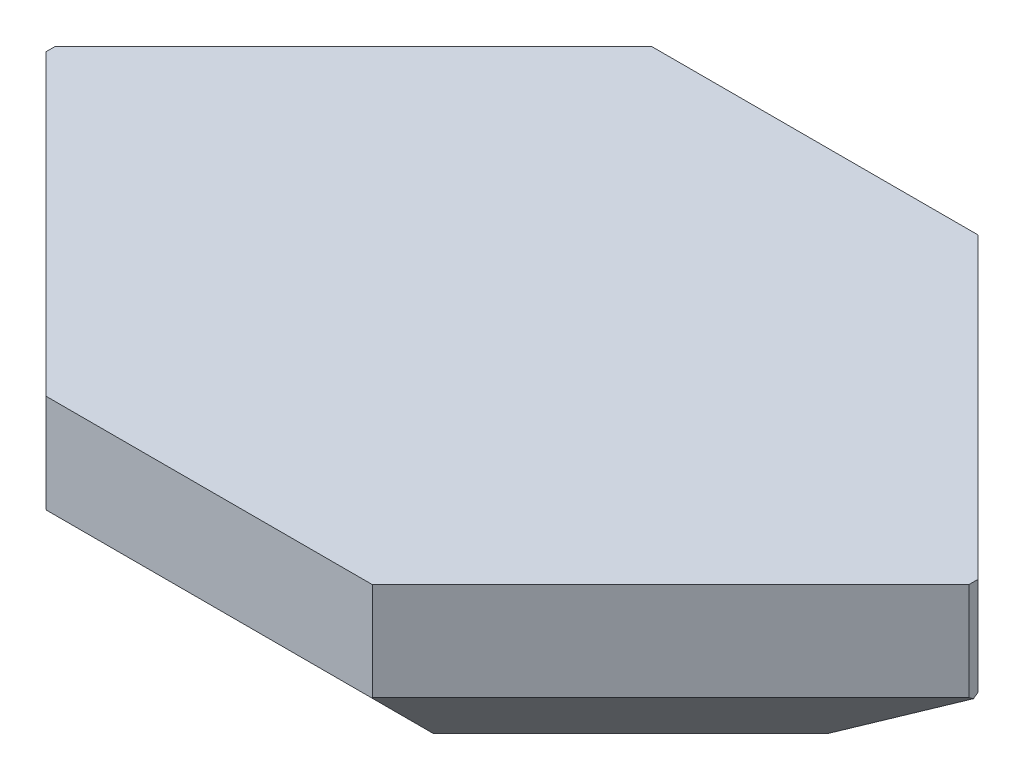
SolidWorks part; units mm, degrees
ref_plane "Front Plane" through (0, 0, 0) normal (0, 0, 1) x (1, 0, 0)
ref_plane "Top Plane" through (0, 0, 0) normal (0, 1, 0) x (1, 0, 0)
ref_plane "Right Plane" through (0, 0, 0) normal (1, 0, 0) x (0, 0, -1)
sketch "Sketch1" plane through (0, 0, 0) normal (0, 1, 0) x (1, 0, 0)
  line L4 (-25.4, 47.1463) -> (25.4, 47.1463)
  line L5 (25.4, 47.1463) -> (72.5463, 0)
  line L6 (72.5463, 0) -> (25.4, -47.1463)
  line L7 (25.4, -47.1463) -> (-25.4, -47.1463)
  line L8 (-25.4, -47.1463) -> (-72.5463, 0)
  line L9 (-72.5463, 0) -> (-25.4, 47.1463)
  line L10 (0, 47.1463) -> (0, -47.1463) construction
  point P9 (0, 0)
  dimension "D1" = 66.675
  dimension "D2" = 50.8
extrude "Boss-Extrude1" add sketch "Sketch1" along normal blind 76.2
ref_plane "Plane1" through (0, 14.5268, 14.5268) normal (0, 0.7071, 0.7071) x (-1, 0, 0)
ref_plane "Plane2" through (0, 10.0367, 10.0367) normal (0, 0.7071, 0.7071) x (-1, 0, 0)
other "SurfaceCut1"
ref_plane "Plane3" through (0, 14.5268, -14.5268) normal (0, 0.7071, -0.7071) x (1, 0, 0)
ref_plane "Plane4" through (0, 10.0367, -10.0367) normal (0, 0.7071, -0.7071) x (1, 0, 0)
other "SurfaceCut2"
ref_plane "Plane5" through (0, 50.8, 0) normal (0, 1, 0) x (1, 0, 0)
other "SurfaceCut3"
chamfer "Chamfer1" distance 16.51 angle 45 4 edges at (-57.183, 50.8, 15.3633) (-57.183, 50.8, -15.3633) (57.183, 50.8, 15.3633) (57.183, 50.8, -15.3633)
chamfer "Chamfer2" distance 1 angle 45 2 edges at (-72.5463, 71.755, 0) (72.5463, 71.755, 0)
sketch "Sketch2" plane through (0, 76.2, 0) normal (0, 1, 0) x (1, 0, 0)
  line L3 (-23.6828, 45.6816) -> (-69.3644, 0)
  line L4 (-69.3644, 0) -> (-23.6828, -45.6816)
  line L5 (-23.6828, -45.6816) -> (-23.6828, 45.6816)
  line L6 (-23.6828, 45.6816) -> (-69.3644, 0)
  line L7 (-69.3644, 0) -> (-23.6828, -45.6816)
  line L8 (-23.6828, -45.6816) -> (-23.6828, 45.6816)
  line L9 (69.3644, 0) -> (23.6828, 45.6816)
  line L10 (23.6827, -45.6816) -> (69.3644, 0)
  line L11 (23.6828, 45.6816) -> (23.6827, -45.6816)
  line L12 (69.3644, 0) -> (23.6828, 45.6816)
  line L13 (23.6827, -45.6816) -> (69.3644, 0)
  line L14 (23.6828, 45.6816) -> (23.6827, -45.6816)
  dimension "D1" = 0.25
  dimension "D2" = 0.25
sketch "Sketch5" plane through (0, 10.0367, -10.0367) normal (0, 0.7071, -0.7071) x (1, 0, 0)
  line L0 (0, -21.2511) -> (0, -86.5119) construction
  line L6 (-25.4, -20.544) -> (-71.8392, -53.3815)
  line L7 (-25.4, -20.544) -> (-71.8392, -53.3815)
  line L8 (-71.8392, -53.3815) -> (-71.8392, -54.3815)
  line L9 (-71.8392, -53.3815) -> (-71.8392, -54.3815)
  line L10 (-71.8392, -54.3815) -> (-25.4, -87.219)
  line L11 (-71.8392, -54.3815) -> (-25.4, -87.219)
  line L21 (-25.4, -87.219) -> (25.4, -87.219)
  line L22 (-25.4, -87.219) -> (25.4, -87.219)
  line L23 (25.4, -87.219) -> (71.8392, -54.3815)
  line L24 (25.4, -87.219) -> (71.8392, -54.3815)
  line L25 (71.8392, -54.3815) -> (71.8392, -53.3815)
  line L26 (71.8392, -54.3815) -> (71.8392, -53.3815)
  line L27 (71.8392, -53.3815) -> (25.4, -20.544)
  line L28 (71.8392, -53.3815) -> (25.4, -20.544)
  line L29 (25.4, -20.544) -> (-25.4, -20.544)
  line L30 (25.4, -20.544) -> (-25.4, -20.544)
  circle A0 centre (0, -53.8815) radius 1.905
  circle A1 centre (0, -53.8815) radius 3.81
  dimension "D2" = 3.81
  dimension "D3" = 7.62
  dimension "D1" = 0
ref_plane "Plane6" through (0, 36.9775, -36.9775) normal (0, 0.7071, -0.7071) x (1, 0, 0)
sketch "Sketch6" plane through (0, 36.9775, -36.9775) normal (0, 0.7071, -0.7071) x (1, 0, 0)
  line L0 (0, -86.5119) -> (0, -21.2511) construction
  line L6 (-25.4, -20.544) -> (-71.8392, -53.3815)
  line L7 (-25.4, -20.544) -> (-71.8392, -53.3815)
  line L8 (-71.8392, -53.3815) -> (-71.8392, -54.3815)
  line L9 (-71.8392, -53.3815) -> (-71.8392, -54.3815)
  line L10 (-71.8392, -54.3815) -> (-25.4, -87.219)
  line L11 (-71.8392, -54.3815) -> (-25.4, -87.219)
  line L21 (-25.4, -87.219) -> (25.4, -87.219)
  line L22 (-25.4, -87.219) -> (25.4, -87.219)
  line L23 (25.4, -87.219) -> (71.8392, -54.3815)
  line L24 (25.4, -87.219) -> (71.8392, -54.3815)
  line L25 (71.8392, -54.3815) -> (71.8392, -53.3815)
  line L26 (71.8392, -54.3815) -> (71.8392, -53.3815)
  line L27 (71.8392, -53.3815) -> (25.4, -20.544)
  line L28 (71.8392, -53.3815) -> (25.4, -20.544)
  line L29 (25.4, -20.544) -> (-25.4, -20.544)
  line L30 (25.4, -20.544) -> (-25.4, -20.544)
  circle A0 centre (0, -53.8815) radius 6.35
  dimension "D2" = 12.7
  dimension "D1" = 0
sketch "Sketch7" plane through (0, 76.2, 0) normal (0, 1, 0) x (1, 0, 0)
  line L2 (-22.225, -38.1) -> (22.225, -38.1) construction
  line L3 (-22.225, -38.1) -> (-22.225, 38.1) construction
  line L4 (-22.225, 38.1) -> (22.225, 38.1) construction
  line L5 (22.225, -38.1) -> (22.225, 38.1) construction
  line L6 (-22.225, -38.1) -> (22.225, 38.1) construction
  line L7 (-22.225, 38.1) -> (22.225, -38.1) construction
  text T0 "Diffusion" font "Times New Roman" height in points 16
  text T1 "<i>Super-Resolution</i>" font "Times New Roman" height in points 16
  point P2 (0, 0)
  dimension "D1" = 76.2
  dimension "D2" = 44.45
sketch "Sketch8" plane through (0, 76.2, 0) normal (0, 1, 0) x (1, 0, 0)
  circle A0 centre (0, 12.7) radius 3 construction
  circle A1 centre (0, 12.7) radius 3
sketch "Sketch9" plane through (0, 50.8, 0) normal (0, -1, 0) x (1, 0, 0)
  line L0 (0, 30.7266) -> (0, -30.7266) construction
  line L1 (-18.4711, 30.7266) -> (18.4711, 30.7266) construction
  line L2 (18.4711, -30.7266) -> (-18.4711, -30.7266) construction
  line L3 (-49.1977, 0) -> (49.1977, 0) construction
  circle A0 centre (0, 0) radius 10.6564
  point P10 (0, 0)
sketch "Sketch10" plane through (0, 76.2, 0) normal (0, 1, 0) x (1, 0, 0)
  line L8 (-25.4, 47.1463) -> (-71.8392, 0.7071)
  line L9 (-71.8392, 0.7071) -> (-71.8392, -0.7071)
  line L10 (-71.8392, -0.7071) -> (-25.4, -47.1463)
  line L11 (-25.4, -47.1463) -> (25.4, -47.1463)
  line L12 (25.4, -47.1463) -> (71.8392, -0.7071)
  line L13 (71.8392, -0.7071) -> (71.8392, 0.7071)
  line L14 (71.8392, 0.7071) -> (25.4, 47.1463)
  line L15 (25.4, 47.1463) -> (-25.4, 47.1463)
  line L16 (-25.4, 47.1463) -> (-71.8392, 0.7071)
  line L17 (-71.8392, 0.7071) -> (-71.8392, -0.7071)
  line L18 (-71.8392, -0.7071) -> (-25.4, -47.1463)
  line L19 (-25.4, -47.1463) -> (25.4, -47.1463)
  line L20 (25.4, -47.1463) -> (71.8392, -0.7071)
  line L21 (71.8392, -0.7071) -> (71.8392, 0.7071)
  line L22 (71.8392, 0.7071) -> (25.4, 47.1463)
  line L23 (25.4, 47.1463) -> (-25.4, 47.1463)
  dimension "D1" = 0
extrude "Boss-Extrude2" add sketch "Sketch10" along normal blind 6.35
